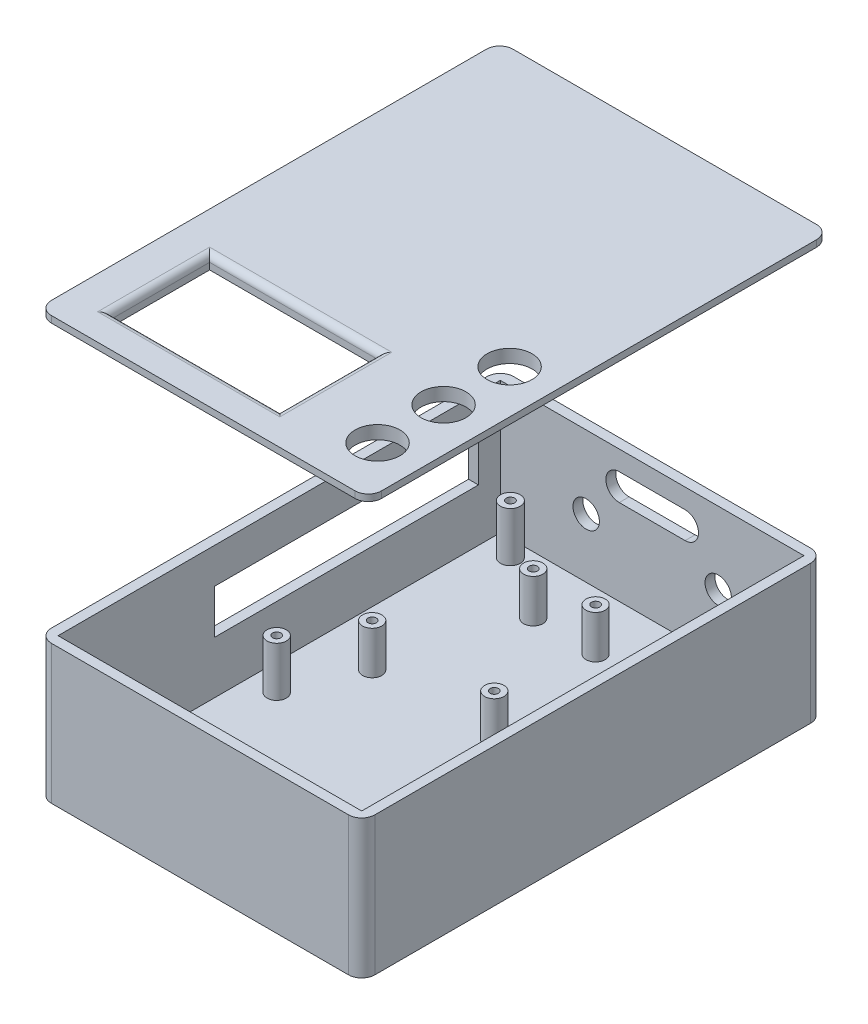
SolidWorks part; units mm, degrees
ref_plane "Front Plane" through (0, 0, 0) normal (0, 0, 1) x (1, 0, 0)
ref_plane "Top Plane" through (0, 0, 0) normal (0, 1, 0) x (1, 0, 0)
ref_plane "Right Plane" through (0, 0, 0) normal (1, 0, 0) x (0, 0, -1)
sketch "Sketch1" plane through (0, 0, 0) normal (0, 1, 0) x (1, 0, 0)
  line L1 (0, 0) -> (124.46, 0)
  line L2 (0, 0) -> (0, 177.8)
  line L3 (0, 177.8) -> (124.46, 177.8)
  line L4 (124.46, 0) -> (124.46, 177.8)
extrude "Boss-Extrude1" add sketch "Sketch1" along normal blind 50.8
sketch "Sketch2" plane through (0, 50.8, 0) normal (0, 1, 0) x (1, 0, 0)
  line L12 (3.81, 173.99) -> (3.81, 3.81)
  line L13 (3.81, 3.81) -> (120.65, 3.81)
  line L14 (120.65, 3.81) -> (120.65, 173.99)
  line L15 (120.65, 173.99) -> (3.81, 173.99)
extrude "Cut-Extrude1" cut sketch "Sketch2" against normal blind 50.8
ref_plane "Plane1" through (0, 154.94, 0) normal (0, 1, 0) x (1, 0, 0)
ref_plane "Plane2" through (0, 0, 0) normal (0, -1, 0) x (-1, 0, 0)
sketch "Sketch4" plane through (0, 0, 0) normal (0, -1, 0) x (-1, 0, 0)
  line L0 (0, 177.8) -> (-124.46, 177.8)
  line L1 (-124.46, 177.8) -> (0, 177.8) construction
  line L2 (-124.46, 0) -> (-124.46, 177.8) construction
  line L3 (-124.46, 177.8) -> (-124.46, 0)
  line L4 (-124.46, 0) -> (0, 0)
  line L5 (0, 0) -> (0, 177.8)
extrude "Boss-Extrude2" add sketch "Sketch4" along normal blind 2.54
sketch "Sketch5" plane through (0, 154.94, 0) normal (0, 1, 0) x (1, 0, 0)
  line L8 (6.35, 172.72) -> (6.35, 6.35)
  line L9 (6.35, 172.72) -> (120.65, 172.72)
  line L10 (120.65, 172.72) -> (120.65, 6.35)
  line L11 (120.65, 6.35) -> (6.35, 6.35)
extrude "Boss-Extrude3" add sketch "Sketch5" along normal blind 2.54 separate body
sketch "Sketch6" plane through (0, 157.48, 0) normal (0, 1, 0) x (1, 0, 0)
  line L0 (127, 0) -> (127, 177.5655)
  line L1 (127, 177.5655) -> (0, 177.5655)
  line L2 (0, 177.5655) -> (0, 0)
  line L3 (0, 0) -> (127, 0)
extrude "Boss-Extrude4" add sketch "Sketch6" along normal blind 2.54
sketch "Sketch7" plane through (0, 160.02, 0) normal (0, 1, 0) x (1, 0, 0)
  line L0 (0, 0) -> (0, 12.7) construction
  line L2 (0, 12.7) -> (15.24, 12.7) construction
  line L3 (0, 88.7827) -> (124.9599, 88.7827) construction
  line L4 (0, 177.5655) -> (0, 0) construction
  line L5 (0, 88.7827) -> (0, 50.7) construction
  line L6 (0, 50.7) -> (15.24, 50.7) construction
  line L7 (15.24, 50.7) -> (15.24, 12.7)
  line L8 (15.24, 12.7) -> (80.24, 12.7)
  line L9 (80.24, 12.7) -> (80.24, 50.7)
  line L10 (80.24, 50.7) -> (15.24, 50.7)
  circle A0 centre (110.2413, 20.32) radius 8.636
  circle A1 centre (110.2413, 45.72) radius 8.636
  circle A2 centre (110.2413, 71.12) radius 8.636
extrude "Cut-Extrude2" cut sketch "Sketch7" against normal blind 7.62
fillet "Fillet1" radius 5.08 1 edges at (124.46, 24.13, 0)
fillet "Fillet2" radius 5.08 1 edges at (127, 158.75, 0)
fillet "Fillet3" radius 5.08 1 edges at (124.46, 24.13, -177.8)
fillet "Fillet4" radius 5.08 1 edges at (0, 24.13, -177.8)
fillet "Fillet5" radius 5.08 1 edges at (0, 24.13, 0)
fillet "Fillet6" radius 5.08 1 edges at (127, 158.75, -177.5655)
fillet "Fillet7" radius 5.08 1 edges at (0, 158.75, -177.5655)
fillet "Fillet8" radius 5.08 1 edges at (0, 158.75, 0)
sketch "Sketch8" plane through (0, 0, 0) normal (0, 1, 0) x (1, 0, 0)
  line L0 (3.81, 173.99) -> (3.81, 88.9) construction
  line L1 (3.81, 173.99) -> (3.81, 3.81) construction
sketch "Sketch9" plane through (0, 0, -177.8) normal (0, 0, -1) x (-1, 0, 0)
  line L0 (-119.38, 50.8) -> (-5.08, 50.8) construction
  line L1 (-62.23, 50.8) -> (-62.23, 38.1) construction
  line L2 (-62.23, 38.1) -> (-49.5744, 38.1) construction
  line L3 (-62.23, 38.1) -> (-74.93, 38.1) construction
  line L4 (-49.5744, 38.1) -> (-74.93, 38.1) construction
  line L5 (-49.5744, 32.9548) -> (-74.93, 32.9548)
  line L6 (-49.5744, 43.2452) -> (-74.93, 43.2452)
  arc A0 (-49.5744, 32.9548) -> (-49.5744, 43.2452) centre (-49.5744, 38.1) ccw
  arc A1 (-74.93, 43.2452) -> (-74.93, 32.9548) centre (-74.93, 38.1) ccw
  point P6 (-62.2522, 38.1)
extrude "Cut-Extrude3" cut sketch "Sketch9" against normal blind 10.16 contours A1 L5 A0 L6
sketch "Sketch10" plane through (0, 0, 0) normal (-1, 0, 0) x (0, 0, 1)
  line L0 (-172.72, 50.8) -> (-147.4141, 50.8) construction
  line L1 (-172.72, 50.8) -> (-5.08, 50.8) construction
  line L2 (-147.4141, 50.8) -> (-127.0941, 50.8) construction
  line L3 (-165.5741, 37.1468) -> (-63.9741, 37.1468)
  line L4 (-165.5741, 20.1468) -> (-63.9741, 20.1468)
  line L5 (-165.5741, 20.1468) -> (-165.5741, 37.1468)
  line L22 (-63.9741, 20.1468) -> (-63.9741, 37.1468)
extrude "Cut-Extrude5" cut sketch "Sketch10" against normal blind 10.16 contours L5 L3 L22 L4
sketch "Sketch12" plane through (0, 0, 0) normal (0, 1, 0) x (1, 0, 0)
  line L0 (3.81, 173.99) -> (3.81, 167.64) construction
  line L1 (3.81, 167.64) -> (13.97, 167.64) construction
  line L2 (3.81, 173.99) -> (114.23, 173.99) construction
  line L3 (120.65, 173.99) -> (3.81, 173.99) construction
  line L4 (13.97, 167.64) -> (13.97, 77.724) construction
  line L5 (13.97, 77.724) -> (109.728, 77.724) construction
  line L7 (109.728, 77.724) -> (109.728, 167.64) construction
  line L8 (109.728, 167.64) -> (13.97, 167.64) construction
  line L12 (62.3, 110.617) -> (62.3, 110.61) construction
  circle A0 centre (14.04, 77.724) radius 1.6
  circle A1 centre (14.04, 77.724) radius 3.7165
  circle A2 centre (109.658, 77.851) radius 1.6
  circle A3 centre (109.658, 77.851) radius 3.81
  circle A4 centre (109.658, 167.64) radius 1.6
  circle A5 centre (109.658, 167.64) radius 3.81
  circle A6 centre (14.04, 167.64) radius 1.6
  circle A7 centre (14.04, 167.64) radius 3.81
sketch "Sketch19" plane through (124.46, 0, 0) normal (1, 0, 0) x (0, 0, -1)
  line L0 (114.3, 24.13) -> (139.7, 24.13) construction
sketch "Sketch20" [suppressed] plane through (160.02, 0, 0) normal (1, 0, 0) x (0, 0, -1)
  text T0 "5 V Input\r\n"
extrude "Boss-Extrude6" [suppressed] add sketch "Sketch20" along normal blind 2.54
sketch "Sketch21" [suppressed] plane through (0, 0, -177.8) normal (0, 0, -1) x (-1, 0, 0)
  text T0 "Output to Rectal Probe\r\n"
extrude "Boss-Extrude7" [suppressed] add sketch "Sketch21" along normal blind 2.54
sketch "Sketch22" plane through (0, 154.94, 0) normal (0, 1, 0) x (1, 0, 0)
  line L0 (132.9426, 0) -> (132.9426, 178.3332)
  line L1 (132.9426, 178.3332) -> (-5.7746, 178.3332)
  line L2 (-5.7746, 178.3332) -> (-5.7746, 0)
  line L3 (-5.7746, 0) -> (132.9426, 0)
ref_plane "Plane3" through (0, 149.86, 0) normal (0, 1, 0) x (1, 0, 0)
sketch "Sketch23" plane through (0, 149.86, 0) normal (0, 1, 0) x (1, 0, 0)
  line L0 (176.3549, -2.341) -> (176.3549, 197.7296)
  line L1 (176.3549, 197.7296) -> (-11.5666, 197.7296)
  line L2 (176.3549, -2.341) -> (-11.5666, -2.341)
  line L3 (-11.5666, -2.341) -> (-11.5666, 197.7296)
sketch "Sketch24" [suppressed] plane through (160.02, 0, 0) normal (1, 0, 0) x (0, 0, -1)
  text T0 "Arduino Input"
extrude "Boss-Extrude8" [suppressed] add sketch "Sketch24" along normal blind 2.54
fillet "Fillet9" radius 2.54 1 edges at (47.74, 160.02, -12.7)
fillet "Fillet10" radius 2.54 2 edges at (80.24, 160.02, -30.43) (80.24, 159.2761, -11.9561)
fillet "Fillet11" radius 2.54 2 edges at (80.9839, 159.2761, -50.7) (49.01, 160.02, -50.7)
fillet "Fillet12" radius 2.54 3 edges at (15.24, 159.2761, -51.4439) (15.24, 160.02, -31.7) (15.24, 159.2761, -11.9561)
ref_plane "Plane4" through (119.38, 50.8, 0) normal (1, 0, 0) x (0, 0, -1)
sketch "Sketch26" plane through (0, 50.8, 0) normal (0, 1, 0) x (1, 0, 0)
sketch "Sketch27" plane through (0, 50.8, 0) normal (0, 1, 0) x (1, 0, 0)
sketch "Sketch28" plane through (0, 0, 0) normal (0, 1, 0) x (1, 0, 0)
  line L0 (3.81, 173.99) -> (3.81, 167.64) construction
  line L1 (3.81, 167.64) -> (13.97, 167.64) construction
  line L2 (13.97, 167.64) -> (13.97, 77.724) construction
  line L3 (13.97, 77.724) -> (109.728, 77.724) construction
  line L4 (13.97, 167.64) -> (109.728, 167.64) construction
  line L5 (109.728, 167.64) -> (109.728, 77.724) construction
sketch "Sketch29" plane through (3.81, 0, 0) normal (1, 0, 0) x (0, 0, -1)
  line L0 (88.9, 0) -> (88.9, 20.1468) construction
  line L1 (165.5741, 20.1468) -> (63.9741, 20.1468) construction
extrude "Boss-Extrude9" add sketch "Sketch12" along normal blind 19.05 contours A6 | A0 | A2 | A4 | A5 | A3 | A7 | A1
sketch "Sketch31" plane through (0, 0, 0) normal (0, 1, 0) x (1, 0, 0)
  line L0 (13.97, 77.724) -> (24.872, 88.626) construction
  line L1 (24.872, 88.626) -> (24.872, 157.0282) construction
  line L2 (24.872, 157.0282) -> (78.339, 157.0282) construction
  line L3 (78.339, 157.0282) -> (78.339, 88.626) construction
  line L4 (78.339, 88.626) -> (24.872, 88.626) construction
  line L5 (24.872, 88.626) -> (24.872, 103.626) construction
  line L6 (24.872, 103.626) -> (24.872, 151.626) construction
  line L7 (24.872, 151.626) -> (38.872, 151.626) construction
  line L8 (38.872, 151.626) -> (62.872, 151.626) construction
  line L9 (24.872, 103.626) -> (71.872, 103.626) construction
  circle A0 centre (24.872, 103.626) radius 1.5999
  circle A1 centre (24.872, 103.626) radius 3.7084
  circle A2 centre (71.862, 103.626) radius 1.5999
  circle A3 centre (71.862, 103.626) radius 3.7084
  circle A4 centre (38.588, 151.886) radius 3.7084
  circle A5 centre (38.588, 151.886) radius 1.5999
  circle A6 centre (62.588, 151.886) radius 3.7084
  circle A7 centre (62.588, 151.886) radius 1.5999
extrude "Boss-Extrude10" add sketch "Sketch31" along normal blind 16.51 contours A2 | A3 | A0 | A1 | A6 | A7 | A5 | A4
sketch "Sketch33" plane through (0, 0, 0) normal (0, 1, 0) x (1, 0, 0)
  circle A0 centre (109.728, 77.724) radius 1.5999
  circle A1 centre (13.97, 77.724) radius 1.5999
  circle A2 centre (71.862, 103.626) radius 1.5977
  circle A3 centre (24.872, 103.626) radius 1.5999
  circle A4 centre (62.588, 151.886) radius 1.5999
  circle A5 centre (38.588, 151.886) radius 1.5999
  circle A6 centre (109.728, 167.64) radius 1.5999
  circle A7 centre (13.97, 167.64) radius 1.5999
extrude "Cut-Extrude13" cut sketch "Sketch33" against normal blind 16.51
sketch "Sketch34" plane through (0, 0, 0) normal (0, 1, 0) x (1, 0, 0)
  line L0 (3.81, 173.99) -> (120.8302, 173.99) construction
  line L1 (120.65, 173.99) -> (3.81, 173.99) construction
sketch "Sketch35" plane through (0, 0, -177.8) normal (0, 0, -1) x (-1, 0, 0)
  line L0 (-62.2522, 32.9548) -> (-62.2522, 22.7948) construction
  line L1 (-49.5744, 32.9548) -> (-74.93, 32.9548) construction
  line L2 (-62.2522, 22.7948) -> (-87.6522, 22.7948) construction
  line L3 (-62.2522, 22.7948) -> (-36.8522, 22.7948) construction
  circle A0 centre (-87.6522, 22.7948) radius 5.08
  circle A1 centre (-36.8522, 22.7948) radius 5.08
extrude "Cut-Extrude14" cut sketch "Sketch35" against normal blind 16.51
